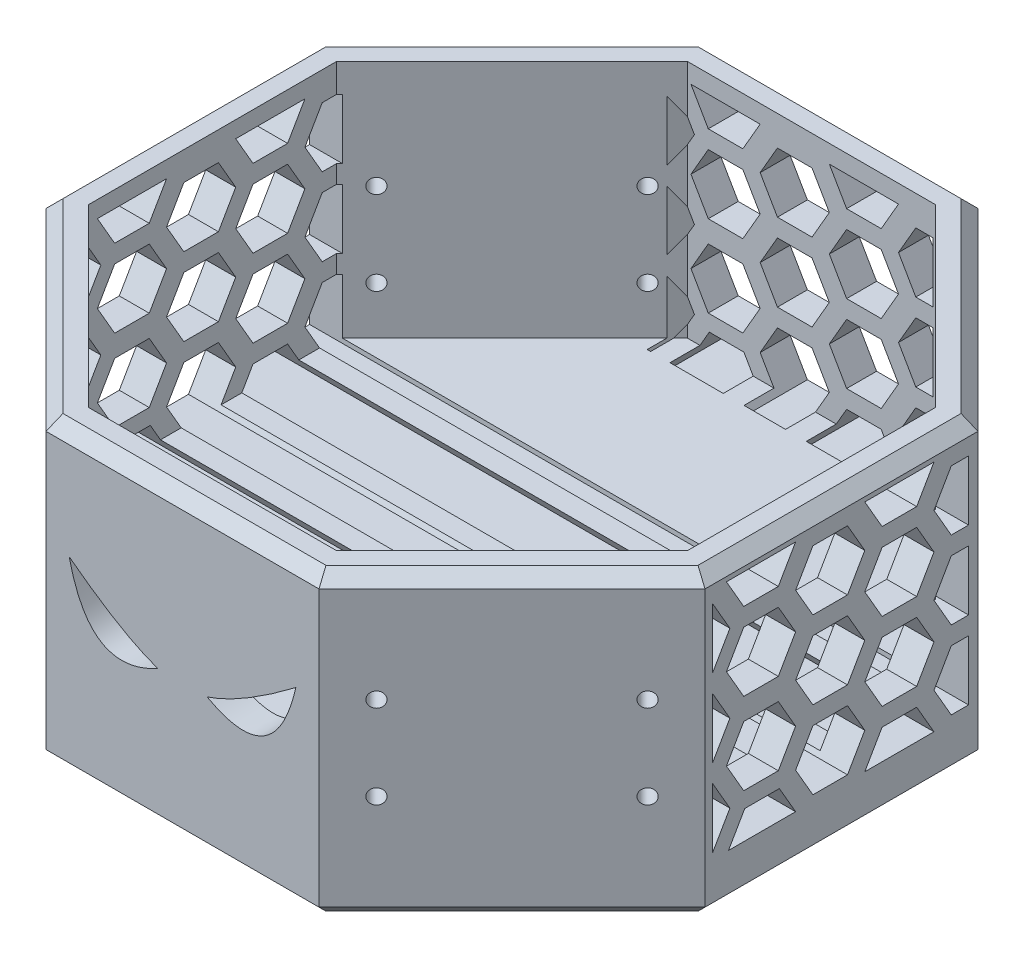
SolidWorks part; units mm, degrees
ref_plane "Plano frontal" through (0, 0, 0) normal (0, 0, 1) x (1, 0, 0)
ref_plane "Plano superior" through (0, 0, 0) normal (0, 1, 0) x (1, 0, 0)
ref_plane "Plano direito" through (0, 0, 0) normal (1, 0, 0) x (0, 0, -1)
sketch "Esboço1" plane through (0, 0, 0) normal (0, 1, 0) x (1, 0, 0)
  line L24 (55, -22.7817) -> (55, 22.7817)
  line L37 (22.7817, 55) -> (-22.7817, 55)
  line L38 (-22.7817, 55) -> (-55, 22.7817)
  line L39 (-55, 22.7817) -> (-55, -22.7817)
  line L40 (-55, -22.7817) -> (-22.7817, -55)
  line L41 (-22.7817, -55) -> (22.7817, -55)
  line L42 (22.7817, -55) -> (55, -22.7817)
  line L43 (55, 22.7817) -> (22.7817, 55)
  circle A0 centre (0, 0) radius 55 construction
  point P1 (-55, 0)
  dimension "D1" = 110
extrude "Ressalto-extrusão1" add sketch "Esboço1" along normal blind 50
sketch "Esboço2" plane through (0, 50, 0) normal (0, 1, 0) x (1, 0, 0)
  line L0 (55, 22.7817) -> (22.7817, 55) construction
  line L1 (50, 20.7107) -> (20.7107, 50)
  line L2 (20.7107, 50) -> (-20.7107, 50)
  line L3 (-20.7107, 50) -> (-50, 20.7107)
  line L4 (-50, 20.7107) -> (-50, -20.7107)
  line L5 (-50, -20.7107) -> (-20.7107, -50)
  line L6 (-20.7107, -50) -> (20.7107, -50)
  line L7 (20.7107, -50) -> (50, -20.7107)
  line L8 (50, -20.7107) -> (50, 20.7107)
  circle A0 centre (0, 0) radius 50 construction
  point P1 (-50, 0)
  dimension "D1" = 5
extrude "Corte-extrusão2" cut sketch "Esboço2" against normal blind 40
hole_wizard "Broca de rosquear para tarraxa de M31" positions "Esboço7" profile "Esboço8" hole size "M3" standard "ISO" end condition through all
sketch "Esboço7" plane through (38.8909, 0, 38.8909) normal (0.7071, 0, 0.7071) x (0.7071, 0, -0.7071)
  line L0 (-16, 32) -> (16, 32) construction
  line L1 (-22.7817, 0) -> (22.7817, 0) construction
  point P0 (-16, 32)
  point P2 (16, 32)
  point P8 (0, 32)
  point P14 (-16, 18)
  point P16 (16, 18)
  dimension "D1" = 32
  dimension "D2" = 32
  dimension "D3" = 14
sketch "Esboço8" plane through (27.5772, 32, 50.2046) normal (0, 1, 0) x (0.7071, 0, -0.7071)
  line L0 (0, 0) -> (0, 132.7817)
  line L1 (0, 132.7817) -> (1.25, 132.7817)
  line L2 (1.25, 132.7817) -> (1.25, 0)
  line L5 (1.25, 0) -> (0, 0)
  line L11 (0, -6.35) -> (0, 107.95) construction
  dimension "Thru Hole Dia." = 2.5
  dimension "Thru Hole Depth" = 132.7817
hole_wizard "Broca de rosquear para tarraxa de M32" positions "Esboço9" profile "Esboço10" hole size "M3" standard "ISO" end condition through all
sketch "Esboço9" plane through (-38.8909, 0, 38.8909) normal (-0.7071, 0, 0.7071) x (0.7071, 0, 0.7071)
  line L0 (-16, 32) -> (16, 32) construction
  line L2 (-22.7817, 0) -> (22.7817, 0) construction
  point P0 (-16, 32)
  point P2 (16, 32)
  point P9 (0, 32)
  point P13 (-16, 18)
  point P15 (16, 18)
  point P20 (0, 0)
  dimension "D1" = 32
  dimension "D2" = 32
  dimension "D3" = 14
sketch "Esboço10" plane through (-50.2046, 32, 27.5772) normal (0, 1, 0) x (0.7071, 0, 0.7071)
  line L0 (0, 0) -> (0, 132.7817)
  line L1 (0, 132.7817) -> (1.25, 132.7817)
  line L2 (1.25, 132.7817) -> (1.25, 0)
  line L5 (1.25, 0) -> (0, 0)
  line L11 (0, -6.35) -> (0, 107.95) construction
  dimension "Thru Hole Dia." = 2.5
  dimension "Thru Hole Depth" = 132.7817
chamfer "Chanfro1" distance 2 angle 45 16 edges at (-55, 0, 0) (-38.8909, 0, -38.8909) (0, 0, -55) (38.8909, 0, -38.8909) (55, 0, 0) (38.8909, 0, 38.8909) (0, 0, 55) (-38.8909, 0, 38.8909) (38.8909, 50, 38.8909) (55, 50, 0) (38.8909, 50, -38.8909) (0, 50, -55) (-38.8909, 50, -38.8909) (-55, 50, 0) (-38.8909, 50, 38.8909) (0, 50, 55)
sketch "Esboço11" plane through (-55, 0, 0) normal (-1, 0, 0) x (0, 0, 1)
  line L12 (18.862, 8.2396) -> (16.1485, 12.9395)
  line L15 (7.6615, 27.2396) -> (4.7748, 32.2396)
  line L53 (4.7748, 32.2396) -> (-0.9987, 32.2396)
  line L169 (-0.9987, 32.2396) -> (-3.8855, 27.2396)
  line L170 (16.1485, 12.9395) -> (10.375, 12.9395)
  line L171 (10.375, 12.9395) -> (7.6615, 8.2396)
  line L172 (-3.8855, 27.2396) -> (-0.9987, 22.2396)
  line L173 (-0.9987, 22.2396) -> (4.7748, 22.2396)
  line L174 (4.7748, 22.2396) -> (7.6615, 27.2396)
  line L175 (-3.8855, 21.2396) -> (-6.7722, 26.2396)
  line L176 (-6.7722, 26.2396) -> (-12.5457, 26.2396)
  line L177 (-12.5457, 26.2396) -> (-15.4325, 21.2396)
  line L178 (-15.4325, 21.2396) -> (-12.5457, 16.2396)
  line L179 (-12.5457, 16.2396) -> (-6.7722, 16.2396)
  line L180 (-6.7722, 16.2396) -> (-3.8855, 21.2396)
  line L181 (7.6615, 40.2396) -> (4.7748, 45.2396)
  line L182 (4.7748, 45.2396) -> (-0.9987, 45.2396)
  line L183 (-0.9987, 45.2396) -> (-3.8855, 40.2396)
  line L184 (-3.8855, 40.2396) -> (-0.9987, 35.2396)
  line L185 (-0.9987, 35.2396) -> (4.7748, 35.2396)
  line L186 (4.7748, 35.2396) -> (7.6615, 40.2396)
  line L187 (7.6615, 14.2396) -> (4.7748, 19.2396)
  line L188 (4.7748, 19.2396) -> (-0.9987, 19.2396)
  line L189 (-0.9987, 19.2396) -> (-3.8855, 14.2396)
  line L190 (-3.8855, 14.2396) -> (-0.9987, 9.2396)
  line L191 (-0.9987, 9.2396) -> (4.7748, 9.2396)
  line L192 (4.7748, 9.2396) -> (7.6615, 14.2396)
  line L193 (7.6615, 8.2396) -> (18.862, 8.2396)
  line L194 (-15.4325, 8.2396) -> (-3.8855, 8.2396)
  line L195 (-3.8855, 8.2396) -> (-6.7722, 13.2396)
  line L196 (-6.7722, 13.2396) -> (-12.5457, 13.2396)
  line L197 (-12.5457, 13.2396) -> (-15.4325, 8.2396)
  line L198 (-15.4325, 47.2396) -> (-3.8855, 47.2396)
  line L199 (-3.8855, 34.2396) -> (-6.7722, 39.2396)
  line L200 (-6.7722, 39.2396) -> (-12.5457, 39.2396)
  line L201 (-12.5457, 39.2396) -> (-15.4325, 34.2396)
  line L202 (-15.4325, 34.2396) -> (-12.5457, 29.2396)
  line L203 (-12.5457, 29.2396) -> (-6.7722, 29.2396)
  line L204 (-6.7722, 29.2396) -> (-3.8855, 34.2396)
  line L205 (-15.4325, 47.2396) -> (-12.5457, 42.2396)
  line L206 (-12.5457, 42.2396) -> (-6.7722, 42.2396)
  line L207 (-6.7722, 42.2396) -> (-3.8855, 47.2396)
  line L208 (-21.206, 45.2396) -> (-21.206, 9.2396) construction
  line L209 (-21.206, 45.2396) -> (-21.206, 35.2396)
  line L210 (-15.4325, 40.2396) -> (-18.3192, 45.2396)
  line L211 (-18.3192, 45.2396) -> (-21.206, 45.2396)
  line L212 (-21.206, 35.2396) -> (-18.3192, 35.2396)
  line L213 (-18.3192, 35.2396) -> (-15.4325, 40.2396)
  line L214 (-15.4325, 27.2396) -> (-18.3192, 32.2396)
  line L215 (-18.3192, 32.2396) -> (-21.206, 32.2396)
  line L216 (-21.206, 32.2396) -> (-21.206, 22.2396)
  line L217 (-21.206, 22.2396) -> (-18.3192, 22.2396)
  line L218 (-18.3192, 22.2396) -> (-15.4325, 27.2396)
  line L219 (-15.4325, 14.2396) -> (-18.3192, 19.2396)
  line L220 (-18.3192, 19.2396) -> (-21.206, 19.2396)
  line L221 (-21.206, 19.2396) -> (-21.206, 9.2396)
  line L222 (-21.206, 9.2396) -> (-18.3192, 9.2396)
  line L223 (-18.3192, 9.2396) -> (-15.4325, 14.2396)
  line L224 (19.2085, 34.2396) -> (16.3218, 39.2396)
  line L225 (16.3218, 39.2396) -> (10.5483, 39.2396)
  line L226 (10.5483, 39.2396) -> (7.6615, 34.2396)
  line L227 (7.6615, 34.2396) -> (10.5483, 29.2396)
  line L228 (10.5483, 29.2396) -> (16.3218, 29.2396)
  line L229 (16.3218, 29.2396) -> (19.2085, 34.2396)
  line L230 (7.6615, 47.2396) -> (10.5483, 42.2396)
  line L231 (10.5483, 42.2396) -> (16.3218, 42.2396)
  line L232 (16.3218, 42.2396) -> (19.2085, 47.2396)
  line L233 (7.6615, 47.2396) -> (19.2085, 47.2396)
  line L234 (21.5179, 45.2396) -> (21.5179, 35.2396)
  line L235 (19.2085, 20.6028) -> (16.3218, 25.6028)
  line L236 (16.3218, 25.6028) -> (10.5483, 25.6028)
  line L237 (10.5483, 25.6028) -> (7.6615, 20.6028)
  line L238 (7.6615, 20.6028) -> (10.5483, 15.6028)
  line L239 (10.5483, 15.6028) -> (16.3218, 15.6028)
  line L240 (16.3218, 15.6028) -> (19.2085, 20.6028)
  line L241 (21.5179, 45.2396) -> (18.6312, 40.2396)
  line L242 (18.6312, 40.2396) -> (21.5179, 35.2396)
  line L243 (21.5179, 45.2396) -> (21.5179, 8.2396) construction
  line L244 (21.5179, 32.2396) -> (21.5179, 22.2396)
  line L245 (18.6312, 27.2396) -> (21.5179, 22.2396)
  line L246 (21.5179, 32.2396) -> (18.6312, 27.2396)
  line L247 (21.5179, 19.2396) -> (21.5179, 9.2396)
  line L248 (18.6312, 14.2396) -> (21.5179, 9.2396)
  line L249 (21.5179, 19.2396) -> (18.6312, 14.2396)
  arc A0 (18.2528, 8.2396) -> (8.2708, 8.2396) centre (13.2618, 7.9395) ccw construction
  circle A2 centre (1.888, 27.2396) radius 5 construction
  circle A3 centre (-9.659, 21.2396) radius 5 construction
  circle A4 centre (1.888, 40.2396) radius 5 construction
  circle A5 centre (1.888, 14.2396) radius 5 construction
  arc A6 (-4.659, 8.2396) -> (-14.659, 8.2396) centre (-9.659, 8.2396) ccw construction
  circle A7 centre (-9.659, 34.2396) radius 5 construction
  arc A8 (-14.659, 47.2396) -> (-4.659, 47.2396) centre (-9.659, 47.2396) ccw construction
  arc A9 (-21.206, 35.2396) -> (-21.206, 45.2396) centre (-21.206, 40.2396) ccw construction
  circle A10 centre (13.435, 34.2396) radius 5 construction
  arc A11 (8.435, 47.2396) -> (18.435, 47.2396) centre (13.435, 47.2396) ccw construction
  circle A12 centre (13.435, 20.6028) radius 5 construction
  arc A13 (21.5179, 44.3221) -> (21.5179, 36.1571) centre (24.4047, 40.2396) ccw construction
  point P52 (13.2618, 8.2396)
  dimension "D1" = 10
  dimension "D2" = 10
  dimension "D3" = 10
  dimension "D4" = 10
  dimension "D6" = 10
  dimension "D9" = 10
  dimension "D12" = 10
  dimension "D15" = 10
  dimension "D5" = 3
  dimension "D7" = 3
  dimension "D8" = 3
  dimension "D10" = 3
  dimension "D11" = 3
  dimension "D13" = 3
  dimension "D14" = 3
  dimension "D16" = 3
  dimension "D17" = 3
  dimension "D18" = 3
  dimension "D19" = 3
extrude "Corte-extrusão3" cut sketch "Esboço11" against normal through all
sketch "Esboço12" plane through (0, 0, -55) normal (0, 0, -1) x (-1, 0, 0)
  line L0 (22.7817, 48) -> (-22.7817, 48) construction
  line L1 (-22.7817, 2) -> (22.7817, 2) construction
  line L2 (22.7817, 48) -> (22.7817, 2) construction
  line L3 (19.7817, 8) -> (17.0682, 12.6999)
  line L4 (8.5812, 27) -> (5.6945, 32)
  line L5 (5.6945, 32) -> (-0.079, 32)
  line L6 (-0.079, 32) -> (-2.9658, 27)
  line L127 (17.0682, 12.6999) -> (11.2947, 12.6999)
  line L128 (11.2947, 12.6999) -> (8.5812, 8)
  line L132 (-2.9658, 27) -> (-0.079, 22)
  line L133 (-0.079, 22) -> (5.6945, 22)
  line L134 (5.6945, 22) -> (8.5812, 27)
  line L135 (-2.9658, 21) -> (-5.8525, 26)
  line L136 (-5.8525, 26) -> (-11.626, 26)
  line L137 (-11.626, 26) -> (-14.5128, 21)
  line L138 (-14.5128, 21) -> (-11.626, 16)
  line L139 (-11.626, 16) -> (-5.8525, 16)
  line L140 (-5.8525, 16) -> (-2.9658, 21)
  line L147 (8.5812, 40) -> (5.6945, 45)
  line L148 (5.6945, 45) -> (-0.079, 45)
  line L149 (-0.079, 45) -> (-2.9658, 40)
  line L150 (-2.9658, 40) -> (-0.079, 35)
  line L151 (-0.079, 35) -> (5.6945, 35)
  line L152 (5.6945, 35) -> (8.5812, 40)
  line L153 (8.5812, 14) -> (5.6945, 19)
  line L154 (5.6945, 19) -> (-0.079, 19)
  line L155 (-0.079, 19) -> (-2.9658, 14)
  line L156 (-2.9658, 14) -> (-0.079, 9)
  line L157 (-0.079, 9) -> (5.6945, 9)
  line L158 (5.6945, 9) -> (8.5812, 14)
  line L159 (8.5812, 8) -> (19.7817, 8)
  line L160 (-14.5128, 8) -> (-2.9658, 8)
  line L161 (14.1815, 2.6999) -> (17.0682, 2.6999) [skipped]
  line L162 (18.5116, 5.1999) -> (19.955, 7.6999) [skipped]
  line L163 (8.408, 7.6999) -> (11.2947, 2.6999) [skipped]
  line L164 (-2.9658, 8) -> (-5.8525, 13)
  line L165 (-5.8525, 13) -> (-11.626, 13)
  line L166 (-11.626, 13) -> (-14.5128, 8)
  line L170 (-14.5128, 47) -> (-2.9658, 47)
  line L171 (-3.361, 7.3154) -> (-1.9177, 9.8154) [skipped]
  line L172 (-11.626, 3) -> (-8.7393, 3) [skipped]
  line L173 (-14.5128, 8) -> (-13.0694, 5.5) [skipped]
  line L174 (-2.9658, 34) -> (-5.8525, 39)
  line L175 (-5.8525, 39) -> (-11.626, 39)
  line L176 (-11.626, 39) -> (-14.5128, 34)
  line L177 (-14.5128, 34) -> (-11.626, 29)
  line L178 (-11.626, 29) -> (-5.8525, 29)
  line L179 (-5.8525, 29) -> (-2.9658, 34)
  line L183 (-14.5128, 47) -> (-11.626, 42)
  line L184 (-11.626, 42) -> (-5.8525, 42)
  line L185 (-5.8525, 42) -> (-2.9658, 47)
  line L186 (-20.2863, 45) -> (-20.2863, 9) construction
  line L187 (-8.7393, 52) -> (-11.626, 52) [skipped]
  line L188 (-13.0694, 49.5) -> (-14.5128, 47) [skipped]
  line L189 (-4.4091, 49.5) -> (-5.8525, 52) [skipped]
  line L190 (-20.2863, 45) -> (-20.2863, 35)
  line L191 (-14.5128, 40) -> (-17.3995, 45)
  line L192 (-17.3995, 45) -> (-20.2863, 45)
  line L195 (-20.2863, 35) -> (-17.3995, 35)
  line L196 (-17.3995, 35) -> (-14.5128, 40)
  line L197 (-14.5128, 27) -> (-17.3995, 32)
  line L198 (-24.6164, 42.5) -> (-26.0598, 40) [skipped]
  line L199 (-24.6164, 37.5) -> (-23.173, 35) [skipped]
  line L200 (-17.3995, 32) -> (-20.2863, 32)
  line L201 (-20.2863, 32) -> (-20.2863, 22)
  line L202 (-20.2863, 22) -> (-17.3995, 22)
  line L203 (-17.3995, 22) -> (-14.5128, 27)
  line L204 (-14.5128, 14) -> (-17.3995, 19)
  line L205 (-17.3995, 19) -> (-20.2863, 19)
  line L206 (-20.2863, 19) -> (-20.2863, 9)
  line L207 (-20.2863, 9) -> (-17.3995, 9)
  line L208 (-17.3995, 9) -> (-14.5128, 14)
  line L210 (20.1282, 34) -> (17.2415, 39)
  line L211 (17.2415, 39) -> (11.468, 39)
  line L212 (11.468, 39) -> (8.5812, 34)
  line L213 (8.5812, 34) -> (11.468, 29)
  line L214 (11.468, 29) -> (17.2415, 29)
  line L215 (17.2415, 29) -> (20.1282, 34)
  line L220 (8.5812, 47) -> (11.468, 42)
  line L221 (11.468, 42) -> (17.2415, 42)
  line L222 (17.2415, 42) -> (20.1282, 47)
  line L223 (8.5812, 47) -> (20.1282, 47)
  line L224 (22.4376, 45) -> (22.4376, 35)
  line L225 (14.3547, 52) -> (11.468, 52) [skipped]
  line L226 (10.0246, 49.5) -> (8.5812, 47) [skipped]
  line L227 (18.6849, 49.5) -> (17.2415, 52) [skipped]
  line L228 (20.1282, 20.3632) -> (17.2415, 25.3632)
  line L229 (17.2415, 25.3632) -> (11.468, 25.3632)
  line L230 (11.468, 25.3632) -> (8.5812, 20.3632)
  line L231 (8.5812, 20.3632) -> (11.468, 15.3632)
  line L232 (11.468, 15.3632) -> (17.2415, 15.3632)
  line L233 (17.2415, 15.3632) -> (20.1282, 20.3632)
  line L236 (22.4376, 45) -> (19.5509, 40)
  line L237 (19.5509, 40) -> (22.4376, 35)
  line L240 (22.4376, 45) -> (22.4376, 8) construction
  line L241 (31.0979, 40) -> (29.6545, 42.5) [skipped]
  line L242 (28.2112, 35) -> (29.6545, 37.5) [skipped]
  line L243 (22.4376, 35) -> (25.3244, 35) [skipped]
  line L244 (25.3244, 45) -> (22.4376, 45) [skipped]
  line L245 (22.4376, 32) -> (22.4376, 22)
  line L246 (19.5509, 27) -> (22.4376, 22)
  line L247 (22.4376, 32) -> (19.5509, 27)
  line L248 (22.4376, 19) -> (22.4376, 9)
  line L249 (19.5509, 14) -> (22.4376, 9)
  line L250 (22.4376, 19) -> (19.5509, 14)
  arc A0 (19.1725, 8) -> (9.1905, 8) centre (14.1815, 7.6999) ccw construction
  circle A1 centre (2.8077, 27) radius 5 construction
  circle A2 centre (-8.7393, 21) radius 5 construction
  circle A3 centre (2.8077, 40) radius 5 construction
  circle A4 centre (2.8077, 14) radius 5 construction
  arc A5 (-3.7393, 8) -> (-13.7393, 8) centre (-8.7393, 8) ccw construction
  circle A6 centre (-8.7393, 34) radius 5 construction
  arc A7 (-13.7393, 47) -> (-3.7393, 47) centre (-8.7393, 47) ccw construction
  arc A8 (-20.2863, 35) -> (-20.2863, 45) centre (-20.2863, 40) ccw construction
  circle A9 centre (14.3547, 34) radius 5 construction
  arc A10 (9.3547, 47) -> (19.3547, 47) centre (14.3547, 47) ccw construction
  circle A11 centre (14.3547, 20.3632) radius 5 construction
  arc A12 (22.4376, 44.0825) -> (22.4376, 35.9175) centre (25.3244, 40) ccw construction
  point P63 (14.1815, 8)
  dimension "D3" = 3
  dimension "D2" = 10
  dimension "D4" = 10
  dimension "D6" = 10
  dimension "D8" = 10
  dimension "D10" = 10
  dimension "D13" = 10
  dimension "D16" = 10
  dimension "D19" = 10
  dimension "D20" = 3
  dimension "D5" = 3
  dimension "D7" = 3
  dimension "D9" = 3
  dimension "D11" = 3
  dimension "D12" = 3
  dimension "D14" = 6
  dimension "D15" = 3
  dimension "D17" = 3
  dimension "D18" = 3
  dimension "D22" = 3
  dimension "D23" = 3
  dimension "D24" = 3
  dimension "D21" = 3
  dimension "D25" = 3
extrude "Corte-extrusão4" cut sketch "Esboço12" against normal blind 10
sketch "Esboço13" plane through (0, 0, 55) normal (0, 0, 1) x (1, 0, 0)
  line L0 (0, 2) -> (0, 48) construction
  line L1 (-22.7817, 2) -> (22.7817, 2) construction
  line L2 (22.7817, 48) -> (-22.7817, 48) construction
  spline S0 degree 2 poles (-18.9179, 31.8128) (-9.7909, 24.9037) (-4.1074, 23.0506) knots 0 0 0 1 1 1
  spline S1 degree 2 poles (-18.9179, 31.8128) (-15.5168, 16.8069) (-4.1074, 23.0506) knots 0 0 0 1 1 1
  spline S2 degree 2 poles (18.9179, 31.8128) (9.7909, 24.9037) (4.1074, 23.0506) knots 0 0 0 1 1 1
  spline S3 degree 2 poles (18.9179, 31.8128) (15.5168, 16.8069) (4.1074, 23.0506) knots 0 0 0 1 1 1
extrude "Corte-extrusão5" cut sketch "Esboço13" against normal blind 10
